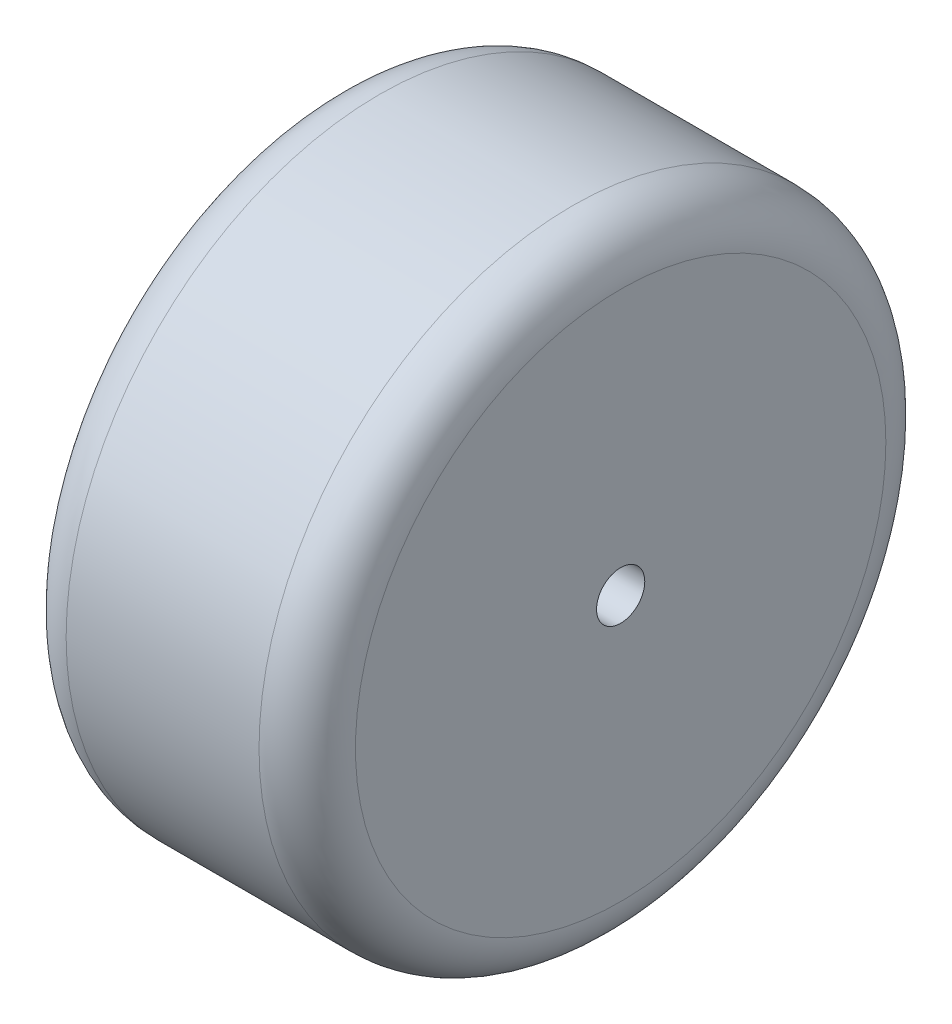
SolidWorks part; units mm, degrees
ref_plane "前基準面" through (0, 0, 0) normal (0, 0, 1) x (1, 0, 0)
ref_plane "上基準面" through (0, 0, 0) normal (0, 1, 0) x (1, 0, 0)
ref_plane "右基準面" through (0, 0, 0) normal (1, 0, 0) x (0, 0, -1)
sketch "草圖1" plane through (0, 0, 0) normal (1, 0, 0) x (0, 0, -1)
  circle A0 centre (0, 0) radius 32.5
  circle A1 centre (0, 0) radius 2.5
  dimension "D1" = 5
  dimension "D2" = 65
extrude "填料-伸長1" add sketch "草圖1" along normal blind 30
fillet "圓角1" radius 5 2 edges at (0, 0, -32.5) (30, 0, -32.5)
